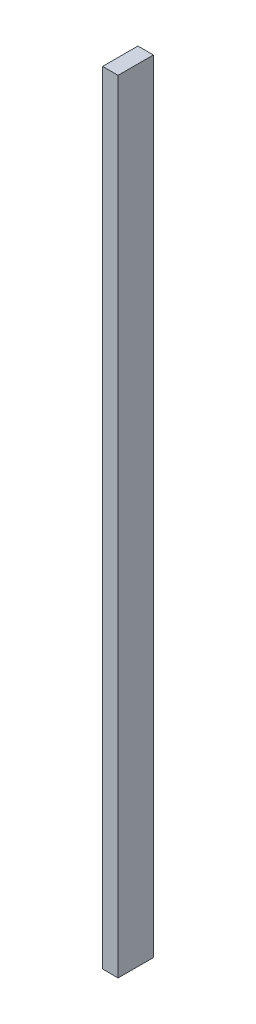
SolidWorks part; units mm, degrees
material "6061-T6 (SS)"
ref_plane "Front" through (0, 0, 0) normal (0, 0, 1) x (1, 0, 0)
ref_plane "Top" through (0, 0, 0) normal (0, 1, 0) x (1, 0, 0)
ref_plane "Right" through (0, 0, 0) normal (1, 0, 0) x (0, 0, -1)
sketch "Sketch1" plane through (0, 0, 0) normal (0, 1, 0) x (1, 0, 0)
  line L1 (-50.8, 115.8875) -> (50.8, 115.8875)
  line L2 (-50.8, 115.8875) -> (-50.8, -115.8875)
  line L3 (-50.8, -115.8875) -> (50.8, -115.8875)
  line L4 (50.8, 115.8875) -> (50.8, -115.8875)
  line L5 (-50.8, 115.8875) -> (50.8, -115.8875) construction
  line L6 (-50.8, -115.8875) -> (50.8, 115.8875) construction
  point P0 (0, 0)
  dimension "D1" = 101.6
  dimension "D2" = 231.775
extrude "Boss-Extrude1" add sketch "Sketch1" along normal blind 5130.8
